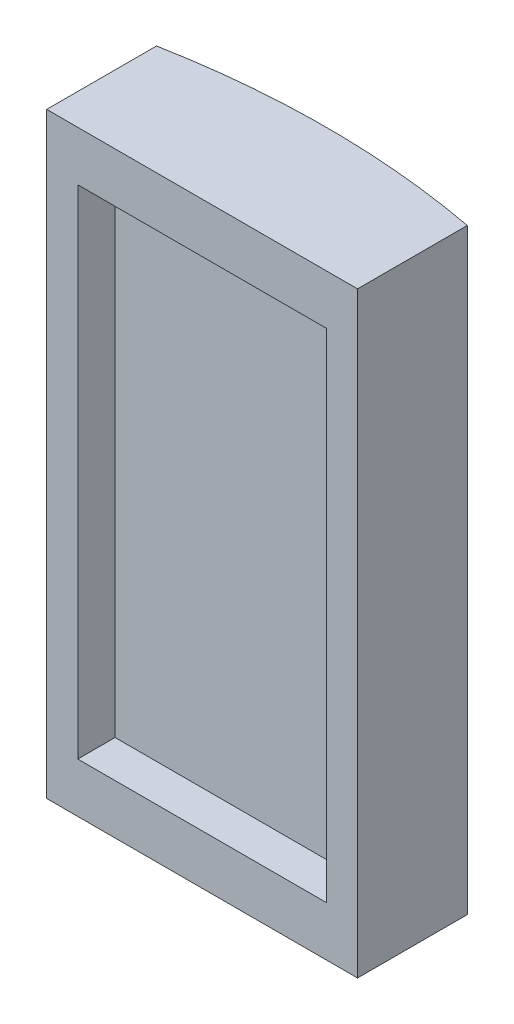
SolidWorks part; units mm, degrees
ref_plane "Front Plane" through (0, 0, 0) normal (0, 0, 1) x (1, 0, 0)
ref_plane "Top Plane" through (0, 0, 0) normal (0, 1, 0) x (1, 0, 0)
ref_plane "Right Plane" through (0, 0, 0) normal (1, 0, 0) x (0, 0, -1)
sketch "Sketch1" plane through (0, 0, 0) normal (0, 0, 1) x (1, 0, 0)
  line L1 (0, 0) -> (25, 0)
  line L2 (0, 0) -> (0, 48)
  line L3 (0, 48) -> (25, 48)
  line L4 (25, 0) -> (25, 48)
  dimension "D1" = 25
  dimension "D2" = 48
extrude "Boss-Extrude1" add sketch "Sketch1" along normal blind 10
sketch "Sketch3" plane through (0, 48, 0) normal (0, 1, 0) x (1, 0, 0)
  line L0 (25, 0) -> (0, 0) construction
  line L2 (0, -10) -> (0, 0) construction
  line L5 (25, -10) -> (25, 0) construction
  line L6 (0, -1.1709) -> (0, -10)
  line L7 (0, -10) -> (25, -10)
  line L8 (25, -10) -> (25, -1.1709)
  arc A0 (25, -1.1709) -> (0, -1.1709) centre (12.5, -67.31) ccw
  dimension "D1" = 134.62
  dimension "D2" = 12.5
extrude "Boss-Extrude2" add sketch "Sketch3" along normal blind 48 contours A0 L6 L7 L8
sketch "Sketch4" plane through (25, 0, 0) normal (1, 0, 0) x (0, 0, -1)
  line L1 (0, 0) -> (-17.0375, 0)
  line L2 (0, 0) -> (0, 48)
  line L3 (0, 48) -> (-17.0375, 48)
  line L4 (-17.0375, 0) -> (-17.0375, 48)
  dimension "D1" = 48
extrude "Cut-Extrude1" cut sketch "Sketch4" against normal blind 48
sketch "Sketch5" plane through (0, 0, 10) normal (0, 0, 1) x (1, 0, 0)
  line L0 (0, 96) -> (0, 48) construction
  line L1 (2.5, 92) -> (22.5, 92)
  line L2 (2.5, 92) -> (2.5, 52)
  line L3 (2.5, 52) -> (22.5, 52)
  line L4 (22.5, 92) -> (22.5, 52)
  line L5 (0, 96) -> (25, 96) construction
  dimension "D1" = 20
  dimension "D2" = 40
  dimension "D3" = 2.5
  dimension "D4" = 4
extrude "Cut-Extrude2" cut sketch "Sketch5" against normal blind 3
